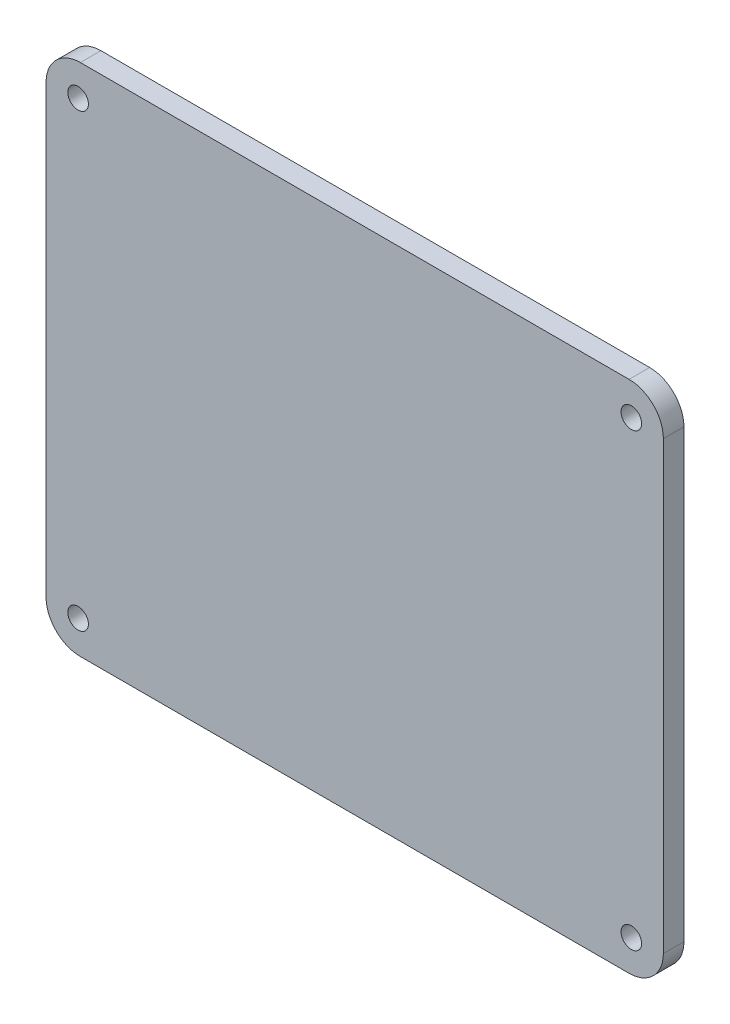
SolidWorks part; units mm, degrees
ref_plane "前视基准面" through (0, 0, 0) normal (0, 0, 1) x (1, 0, 0)
ref_plane "上视基准面" through (0, 0, 0) normal (0, 1, 0) x (1, 0, 0)
ref_plane "右视基准面" through (0, 0, 0) normal (1, 0, 0) x (0, 0, -1)
sketch "草图1" plane through (0, 0, 0) normal (0, 0, 1) x (1, 0, 0)
  line L1 (-40, 37.5) -> (40, 37.5)
  line L2 (-45, 32.5) -> (-45, -32.5)
  line L3 (-40, -37.5) -> (40, -37.5)
  line L4 (45, 32.5) -> (45, -32.5)
  line L5 (0, -37.5) -> (0, 37.5) construction
  line L6 (-45, 0) -> (45, 0) construction
  arc A0 (-45, -32.5) -> (-40, -37.5) centre (-40, -32.5) ccw
  arc A1 (40, -37.5) -> (45, -32.5) centre (40, -32.5) ccw
  arc A2 (40, 37.5) -> (45, 32.5) centre (40, 32.5) cw
  arc A3 (-40, 37.5) -> (-45, 32.5) centre (-40, 32.5) ccw
  point P0 (0, 0)
  point P8 (45, -37.5)
  point P11 (45, 37.5)
  point P15 (-45, 37.5)
  dimension "D3" = 5
  dimension "D1" = 90
  dimension "D2" = 75
extrude "凸台-拉伸1" add sketch "草图1" along normal blind 3
sketch "草图2" plane through (0, 0, 3) normal (0, 0, 1) x (1, 0, 0)
  circle A0 centre (40.3284, 32.8284) radius 1.5
  circle A1 centre (-40.3284, 32.8284) radius 1.5
  circle A2 centre (-40.3284, -32.8284) radius 1.5
  circle A3 centre (40.3284, -32.8284) radius 1.5
  dimension "D1" = 3
  dimension "D2" = 3
  dimension "D3" = 3
  dimension "D4" = 3
extrude "切除-拉伸1" cut sketch "草图2" against normal blind 10
